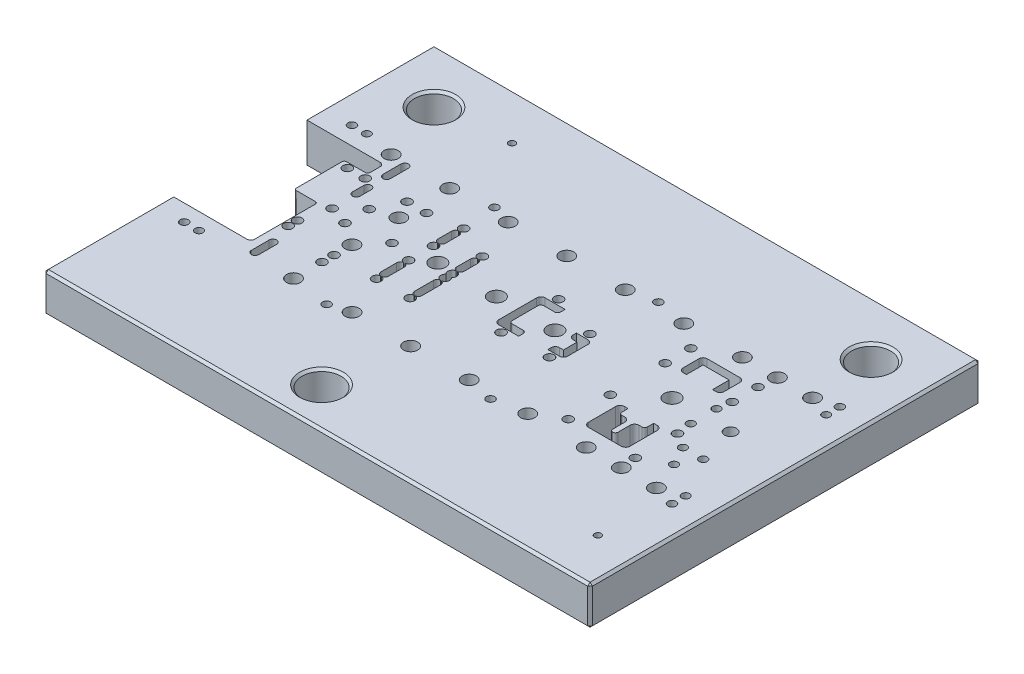
SolidWorks part; units mm, degrees
material "Plain Carbon Steel"
ref_plane "Front Plane" through (0, 0, 0) normal (0, 0, 1) x (1, 0, 0)
ref_plane "Top Plane" through (0, 0, 0) normal (0, 1, 0) x (1, 0, 0)
ref_plane "Right Plane" through (0, 0, 0) normal (1, 0, 0) x (0, 0, -1)
sketch "Sketch1" plane through (0, 0, 0) normal (0, 1, 0) x (1, 0, 0)
  line L1 (-350, -250) -> (350, -250)
  line L2 (-350, -250) -> (-350, 250)
  line L3 (-350, 250) -> (350, 250)
  line L4 (350, -250) -> (350, 250)
  line L5 (-350, -250) -> (350, 250) construction
  line L6 (-350, 250) -> (350, -250) construction
  point P0 (0, 0)
  dimension "D1" = 700
  dimension "D2" = 500
extrude "Boss-Extrude1" add sketch "Sketch1" against normal blind 50
sketch "Sketch2" plane through (0, 0, 0) normal (0, 1, 0) x (1, 0, 0)
  line L0 (350, 250) -> (-350, 250) construction
  line L1 (-350, 250) -> (-350, -250) construction
  line L2 (350, -250) -> (350, 250) construction
  line L3 (-350, -250) -> (350, -250) construction
  circle A0 centre (-280, 180) radius 25
  circle A1 centre (280, 180) radius 25
  circle A2 centre (-44, -200) radius 25
  dimension "D1" = 50
  dimension "D2" = 70
  dimension "D3" = 70
  dimension "D4" = 70
  dimension "D5" = 50
  dimension "D6" = 44
extrude "Cut-Extrude1" cut sketch "Sketch2" against normal up to next
sketch "Sketch3" plane through (0, -50, 0) normal (0, -1, 0) x (1, 0, 0)
  line L0 (178.7436, 30.0264) -> (178.7436, 38.14) construction
  line L1 (182.13, 41.5264) -> (186.13, 41.5264) construction
  line L2 (191.7436, 47.14) -> (191.7436, 62.64) construction
  line L3 (198.5164, 62.64) -> (198.5164, 47.14) construction
  line L4 (204.13, 41.5264) -> (208.13, 41.5264) construction
  line L5 (211.5164, 38.14) -> (211.5164, 30.0264) construction
  line L6 (174.13, 30.0264) -> (178.7436, 30.0264) construction
  line L7 (168.5164, 70.64) -> (168.5164, 35.64) construction
  line L8 (216.13, 76.2536) -> (174.13, 76.2536) construction
  line L9 (211.5164, 30.0264) -> (216.13, 30.0264) construction
  line L10 (221.7436, 35.64) -> (221.7436, 70.64) construction
  line L11 (216.13, -45.0677) -> (211.8377, -45.0677) construction
  line L12 (221.4223, -70.64) -> (221.4223, -50.36) construction
  line L13 (174.13, -75.9323) -> (216.13, -75.9323) construction
  line L14 (178.4223, -45.0677) -> (174.13, -45.0677) construction
  line L15 (168.8377, -50.36) -> (168.8377, -70.64) construction
  line L16 (178.4223, -66.3477) -> (178.4223, -45.0677) construction
  line L17 (211.8377, -66.3477) -> (178.4223, -66.3477) construction
  line L18 (211.8377, -45.0677) -> (211.8377, -66.3477) construction
  line L19 (178.7436, 30.0264) -> (178.7436, 38.14)
  line L20 (182.13, 41.5264) -> (186.13, 41.5264)
  line L21 (191.7436, 47.14) -> (191.7436, 62.64)
  line L22 (198.5164, 62.64) -> (198.5164, 47.14)
  line L23 (204.13, 41.5264) -> (208.13, 41.5264)
  line L24 (211.5164, 38.14) -> (211.5164, 30.0264)
  line L25 (174.13, 30.0264) -> (178.7436, 30.0264)
  line L26 (168.5164, 70.64) -> (168.5164, 35.64)
  line L27 (216.13, 76.2536) -> (174.13, 76.2536)
  line L28 (211.5164, 30.0264) -> (216.13, 30.0264)
  line L29 (221.7436, 35.64) -> (221.7436, 70.64)
  line L30 (216.13, -45.0677) -> (211.8377, -45.0677)
  line L31 (221.4223, -70.64) -> (221.4223, -50.36)
  line L32 (174.13, -75.9323) -> (216.13, -75.9323)
  line L33 (178.4223, -45.0677) -> (174.13, -45.0677)
  line L34 (168.8377, -50.36) -> (168.8377, -70.64)
  line L35 (178.4223, -66.3477) -> (178.4223, -45.0677)
  line L36 (211.8377, -66.3477) -> (178.4223, -66.3477)
  line L37 (211.8377, -45.0677) -> (211.8377, -66.3477)
  line L38 (72.3377, 6.3477) -> (72.3377, -11.0677) construction
  line L39 (67.13, 6.3477) -> (72.3377, 6.3477) construction
  line L40 (61.8377, 15.9323) -> (61.8377, 11.64) construction
  line L41 (72.3377, -11.0677) -> (67.13, -11.0677) construction
  line L42 (61.8377, -16.36) -> (61.8377, -20.6523) construction
  line L43 (76.63, 15.9323) -> (61.8377, 15.9323) construction
  line L44 (81.9223, -15.36) -> (81.9223, 10.64) construction
  line L45 (61.8377, -20.6523) -> (76.63, -20.6523) construction
  line L46 (72.3377, 6.3477) -> (72.3377, -11.0677)
  line L47 (67.13, 6.3477) -> (72.3377, 6.3477)
  line L48 (61.8377, 15.9323) -> (61.8377, 11.64)
  line L49 (72.3377, -11.0677) -> (67.13, -11.0677)
  line L50 (61.8377, -16.36) -> (61.8377, -20.6523)
  line L51 (76.63, 15.9323) -> (61.8377, 15.9323)
  line L52 (81.9223, -15.36) -> (81.9223, 10.64)
  line L53 (61.8377, -20.6523) -> (76.63, -20.6523)
  line L54 (28.4223, 19.9323) -> (2.63, 19.9323) construction
  line L55 (-2.6623, 14.64) -> (-2.6623, -34.36) construction
  line L56 (2.63, -39.6523) -> (28.4223, -39.6523) construction
  line L57 (28.4223, 14.14) -> (28.4223, 19.9323) construction
  line L58 (10.63, 10.3477) -> (24.63, 10.3477) construction
  line L59 (6.9223, -26.36) -> (6.9223, 6.64) construction
  line L60 (24.63, -30.0677) -> (10.63, -30.0677) construction
  line L61 (28.4223, -39.6523) -> (28.4223, -33.86) construction
  line L62 (28.4223, 19.9323) -> (2.63, 19.9323)
  line L63 (-2.6623, 14.64) -> (-2.6623, -34.36)
  line L64 (2.63, -39.6523) -> (28.4223, -39.6523)
  line L65 (28.4223, 14.14) -> (28.4223, 19.9323)
  line L66 (10.63, 10.3477) -> (24.63, 10.3477)
  line L67 (6.9223, -26.36) -> (6.9223, 6.64)
  line L68 (24.63, -30.0677) -> (10.63, -30.0677)
  line L69 (28.4223, -39.6523) -> (28.4223, -33.86)
  line L70 (-131.2322, 36.69) -> (-131.2322, 16.59) construction
  line L71 (-121.5078, 16.59) -> (-121.5078, 36.69) construction
  line L72 (-88.1623, 36.69) -> (-88.1623, 12.59) construction
  line L73 (-78.5777, 12.59) -> (-78.5777, 36.69) construction
  line L74 (-131.1623, -36.31) -> (-131.1623, -53.91) construction
  line L75 (-121.5777, -53.91) -> (-121.5777, -36.31) construction
  line L76 (-88.1623, -17.31) -> (-88.1623, -34.91) construction
  line L77 (-78.5777, -34.91) -> (-78.5777, -17.31) construction
  line L78 (-131.2322, 36.69) -> (-131.2322, 16.59)
  line L79 (-121.5078, 16.59) -> (-121.5078, 36.69)
  line L80 (-88.1623, 36.69) -> (-88.1623, 12.59)
  line L81 (-78.5777, 12.59) -> (-78.5777, 36.69)
  line L82 (-131.1623, -36.31) -> (-131.1623, -53.91)
  line L83 (-121.5777, -53.91) -> (-121.5777, -36.31)
  line L84 (-88.1623, -17.31) -> (-88.1623, -34.91)
  line L85 (-78.5777, -34.91) -> (-78.5777, -17.31)
  line L86 (-238.1623, -72.87) -> (-238.1623, -95.77) construction
  line L87 (-228.5777, -95.77) -> (-228.5777, -72.87) construction
  line L88 (-238.1623, 95.77) -> (-238.1623, 72.87) construction
  line L89 (-228.5777, 72.87) -> (-228.5777, 95.77) construction
  line L90 (-238.1623, -72.87) -> (-238.1623, -95.77)
  line L91 (-228.5777, -95.77) -> (-228.5777, -72.87)
  line L92 (-238.1623, 95.77) -> (-238.1623, 72.87)
  line L93 (-228.5777, 72.87) -> (-228.5777, 95.77)
  line L94 (-228.5777, -48.36) -> (-228.5777, -33.86) construction
  line L95 (-238.1623, -33.86) -> (-238.1623, -48.36) construction
  line L96 (-228.5777, -48.36) -> (-228.5777, -33.86)
  line L97 (-238.1623, -33.86) -> (-238.1623, -48.36)
  arc A0 (182.13, 41.5264) -> (178.7436, 38.14) centre (182.13, 38.14) ccw construction
  arc A1 (186.13, 41.5264) -> (191.7436, 47.14) centre (186.13, 47.14) ccw construction
  arc A2 (198.5164, 62.64) -> (191.7436, 62.64) centre (195.13, 62.64) ccw construction
  arc A3 (198.5164, 47.14) -> (204.13, 41.5264) centre (204.13, 47.14) ccw construction
  arc A4 (211.5164, 38.14) -> (208.13, 41.5264) centre (208.13, 38.14) ccw construction
  arc A5 (168.5164, 35.64) -> (174.13, 30.0264) centre (174.13, 35.64) ccw construction
  arc A6 (174.13, 76.2536) -> (168.5164, 70.64) centre (174.13, 70.64) ccw construction
  arc A7 (221.7436, 70.64) -> (216.13, 76.2536) centre (216.13, 70.64) ccw construction
  arc A8 (216.13, 30.0264) -> (221.7436, 35.64) centre (216.13, 35.64) ccw construction
  arc A9 (221.4223, -50.36) -> (216.13, -45.0677) centre (216.13, -50.36) ccw construction
  arc A10 (216.13, -75.9323) -> (221.4223, -70.64) centre (216.13, -70.64) ccw construction
  arc A11 (168.8377, -70.64) -> (174.13, -75.9323) centre (174.13, -70.64) ccw construction
  arc A12 (174.13, -45.0677) -> (168.8377, -50.36) centre (174.13, -50.36) ccw construction
  arc A13 (182.13, 41.5264) -> (178.7436, 38.14) centre (182.13, 38.14) ccw
  arc A14 (186.13, 41.5264) -> (191.7436, 47.14) centre (186.13, 47.14) ccw
  arc A15 (198.5164, 62.64) -> (191.7436, 62.64) centre (195.13, 62.64) ccw
  arc A16 (198.5164, 47.14) -> (204.13, 41.5264) centre (204.13, 47.14) ccw
  arc A17 (211.5164, 38.14) -> (208.13, 41.5264) centre (208.13, 38.14) ccw
  arc A18 (168.5164, 35.64) -> (174.13, 30.0264) centre (174.13, 35.64) ccw
  arc A19 (174.13, 76.2536) -> (168.5164, 70.64) centre (174.13, 70.64) ccw
  arc A20 (221.7436, 70.64) -> (216.13, 76.2536) centre (216.13, 70.64) ccw
  arc A21 (216.13, 30.0264) -> (221.7436, 35.64) centre (216.13, 35.64) ccw
  arc A22 (221.4223, -50.36) -> (216.13, -45.0677) centre (216.13, -50.36) ccw
  arc A23 (216.13, -75.9323) -> (221.4223, -70.64) centre (216.13, -70.64) ccw
  arc A24 (168.8377, -70.64) -> (174.13, -75.9323) centre (174.13, -70.64) ccw
  arc A25 (174.13, -45.0677) -> (168.8377, -50.36) centre (174.13, -50.36) ccw
  circle A26 centre (270.13, 62.64) radius 5.1136 construction
  circle A27 centre (283.13, 38.14) radius 5.1136 construction
  circle A28 centre (257.13, 38.14) radius 5.1136 construction
  circle A29 centre (235.63, 6.64) radius 5.1136 construction
  circle A30 centre (270.13, -9.86) radius 7.6136 construction
  circle A31 centre (235.63, -26.36) radius 5.1136 construction
  circle A32 centre (270.13, 62.64) radius 5.1136
  circle A33 centre (283.13, 38.14) radius 5.1136
  circle A34 centre (257.13, 38.14) radius 5.1136
  circle A35 centre (235.63, 6.64) radius 5.1136
  circle A36 centre (270.13, -9.86) radius 7.6136
  circle A37 centre (235.63, -26.36) radius 5.1136
  arc A38 (61.8377, 11.64) -> (67.13, 6.3477) centre (67.13, 11.64) ccw construction
  arc A39 (67.13, -11.0677) -> (61.8377, -16.36) centre (67.13, -16.36) ccw construction
  arc A40 (81.9223, 10.64) -> (76.63, 15.9323) centre (76.63, 10.64) ccw construction
  arc A41 (76.63, -20.6523) -> (81.9223, -15.36) centre (76.63, -15.36) ccw construction
  arc A42 (61.8377, 11.64) -> (67.13, 6.3477) centre (67.13, 11.64) ccw
  arc A43 (67.13, -11.0677) -> (61.8377, -16.36) centre (67.13, -16.36) ccw
  arc A44 (81.9223, 10.64) -> (76.63, 15.9323) centre (76.63, 10.64) ccw
  arc A45 (76.63, -20.6523) -> (81.9223, -15.36) centre (76.63, -15.36) ccw
  arc A46 (2.63, 19.9323) -> (-2.6623, 14.64) centre (2.63, 14.64) ccw construction
  arc A47 (-2.6623, -34.36) -> (2.63, -39.6523) centre (2.63, -34.36) ccw construction
  arc A48 (24.63, 10.3477) -> (28.4223, 14.14) centre (24.63, 14.14) ccw construction
  arc A49 (10.63, 10.3477) -> (6.9223, 6.64) centre (10.63, 6.64) ccw construction
  arc A50 (6.9223, -26.36) -> (10.63, -30.0677) centre (10.63, -26.36) ccw construction
  arc A51 (28.4223, -33.86) -> (24.63, -30.0677) centre (24.63, -33.86) ccw construction
  arc A52 (2.63, 19.9323) -> (-2.6623, 14.64) centre (2.63, 14.64) ccw
  arc A53 (-2.6623, -34.36) -> (2.63, -39.6523) centre (2.63, -34.36) ccw
  arc A54 (24.63, 10.3477) -> (28.4223, 14.14) centre (24.63, 14.14) ccw
  arc A55 (10.63, 10.3477) -> (6.9223, 6.64) centre (10.63, 6.64) ccw
  arc A56 (6.9223, -26.36) -> (10.63, -30.0677) centre (10.63, -26.36) ccw
  arc A57 (28.4223, -33.86) -> (24.63, -30.0677) centre (24.63, -33.86) ccw
  arc A58 (-121.5078, 36.69) -> (-131.2322, 36.69) centre (-126.37, 36.69) ccw construction
  arc A59 (-131.2322, 16.59) -> (-121.5078, 16.59) centre (-126.37, 16.59) ccw construction
  arc A60 (-78.5777, 36.69) -> (-88.1623, 36.69) centre (-83.37, 36.69) ccw construction
  arc A61 (-88.1623, 12.59) -> (-78.5777, 12.59) centre (-83.37, 12.59) ccw construction
  arc A62 (-121.5777, -36.31) -> (-131.1623, -36.31) centre (-126.37, -36.31) ccw construction
  arc A63 (-131.1623, -53.91) -> (-121.5777, -53.91) centre (-126.37, -53.91) ccw construction
  arc A64 (-78.5777, -17.31) -> (-88.1623, -17.31) centre (-83.37, -17.31) ccw construction
  arc A65 (-88.1623, -34.91) -> (-78.5777, -34.91) centre (-83.37, -34.91) ccw construction
  arc A66 (-121.5078, 36.69) -> (-131.2322, 36.69) centre (-126.37, 36.69) ccw
  arc A67 (-131.2322, 16.59) -> (-121.5078, 16.59) centre (-126.37, 16.59) ccw
  arc A68 (-78.5777, 36.69) -> (-88.1623, 36.69) centre (-83.37, 36.69) ccw
  arc A69 (-88.1623, 12.59) -> (-78.5777, 12.59) centre (-83.37, 12.59) ccw
  arc A70 (-121.5777, -36.31) -> (-131.1623, -36.31) centre (-126.37, -36.31) ccw
  arc A71 (-131.1623, -53.91) -> (-121.5777, -53.91) centre (-126.37, -53.91) ccw
  arc A72 (-78.5777, -17.31) -> (-88.1623, -17.31) centre (-83.37, -17.31) ccw
  arc A73 (-88.1623, -34.91) -> (-78.5777, -34.91) centre (-83.37, -34.91) ccw
  arc A74 (-228.5777, -72.87) -> (-238.1623, -72.87) centre (-233.37, -72.87) ccw construction
  arc A75 (-238.1623, -95.77) -> (-228.5777, -95.77) centre (-233.37, -95.77) ccw construction
  arc A76 (-228.5777, 95.77) -> (-238.1623, 95.77) centre (-233.37, 95.77) ccw construction
  arc A77 (-238.1623, 72.87) -> (-228.5777, 72.87) centre (-233.37, 72.87) ccw construction
  arc A78 (-228.5777, -72.87) -> (-238.1623, -72.87) centre (-233.37, -72.87) ccw
  arc A79 (-238.1623, -95.77) -> (-228.5777, -95.77) centre (-233.37, -95.77) ccw
  arc A80 (-228.5777, 95.77) -> (-238.1623, 95.77) centre (-233.37, 95.77) ccw
  arc A81 (-238.1623, 72.87) -> (-228.5777, 72.87) centre (-233.37, 72.87) ccw
  arc A82 (-228.5777, -33.86) -> (-238.1623, -33.86) centre (-233.37, -33.86) ccw construction
  arc A83 (-238.1623, -48.36) -> (-228.5777, -48.36) centre (-233.37, -48.36) ccw construction
  arc A84 (-228.5777, -33.86) -> (-238.1623, -33.86) centre (-233.37, -33.86) ccw
  arc A85 (-238.1623, -48.36) -> (-228.5777, -48.36) centre (-233.37, -48.36) ccw
extrude "Cut-Extrude2" cut sketch "Sketch3" against normal up to next
sketch "Sketch4" plane through (0, 0, 0) normal (0, 1, 0) x (1, 0, 0)
  circle A0 centre (-29.87, -100) radius 9 construction
  circle A1 centre (45.13, -100) radius 9 construction
  circle A2 centre (120.13, -100) radius 9 construction
  circle A3 centre (-104.87, 9.86) radius 10 construction
  circle A4 centre (-29.87, 9.86) radius 10 construction
  circle A5 centre (45.13, 9.86) radius 10 construction
  circle A6 centre (195.13, 9.86) radius 10 construction
  circle A7 centre (-104.87, 100) radius 9 construction
  circle A8 centre (-29.87, 100) radius 9 construction
  circle A9 centre (45.13, 100) radius 9 construction
  circle A10 centre (120.13, 100) radius 9 construction
  circle A11 centre (195.13, 100) radius 9 construction
  circle A12 centre (240, 100) radius 9 construction
  circle A13 centre (285, 100) radius 9 construction
  circle A14 centre (195.13, -100) radius 9 construction
  circle A15 centre (240, -100) radius 9 construction
  circle A16 centre (285, -100) radius 9 construction
  circle A17 centre (-29.87, -100) radius 9
  circle A18 centre (45.13, -100) radius 9
  circle A19 centre (120.13, -100) radius 9
  circle A20 centre (-104.87, 9.86) radius 10
  circle A21 centre (-29.87, 9.86) radius 10
  circle A22 centre (45.13, 9.86) radius 10
  circle A23 centre (195.13, 9.86) radius 10
  circle A24 centre (-104.87, 100) radius 9
  circle A25 centre (-29.87, 100) radius 9
  circle A26 centre (45.13, 100) radius 9
  circle A27 centre (120.13, 100) radius 9
  circle A28 centre (195.13, 100) radius 9
  circle A29 centre (240, 100) radius 9
  circle A30 centre (285, 100) radius 9
  circle A31 centre (195.13, -100) radius 9
  circle A32 centre (240, -100) radius 9
  circle A33 centre (285, -100) radius 9
  circle A34 centre (-179.87, -25.14) radius 9 construction
  circle A35 centre (-179.87, 100) radius 9
  circle A36 centre (-179.87, 100) radius 9
  circle A37 centre (-179.87, -100) radius 9
  circle A38 centre (-179.87, -100) radius 9
  circle A39 centre (-104.87, -100) radius 9
  circle A40 centre (-104.87, -100) radius 9
  circle A41 centre (-254.87, 100) radius 9
  circle A42 centre (-254.87, 100) radius 9
  circle A43 centre (-179.87, 34.86) radius 9 construction
  circle A44 centre (-179.87, -25.14) radius 9
  circle A45 centre (-179.87, 34.86) radius 9
  dimension "D1" = 0
  dimension "D2" = 0
  dimension "D3" = 0
  dimension "D4" = 0
extrude "Cut-Extrude3" cut sketch "Sketch4" against normal blind 23
hole_wizard "Ø11.5 (11.5) Diameter Hole1" positions "Sketch8" profile "Sketch7" hole size "Ø11.5" standard "ISO" end condition through all
sketch "Sketch8" plane through (0, -50, 0) normal (0, -1, 0) x (-1, 0, 0)
  point P0 (267.87, 56.92)
  point P3 (245.0007, 56.92)
  point P6 (232.87, 2.36)
  point P9 (208.37, -5.64)
  point P12 (208.37, 25.36)
  point P15 (241.62, -33.14)
  point P18 (241.62, -45.14)
  point P21 (179.87, -48.14)
  point P24 (179.87, -63.64)
  point P27 (192.37, 57.86)
  point P30 (167.37, 57.86)
  point P33 (126.37, 64.36)
  point P36 (126.37, 25.86)
  point P39 (126.37, -47.14)
  point P42 (126.37, -6.14)
  point P45 (156.12, 2.36)
  point P48 (83.37, -47.14)
  point P51 (83.37, -2.14)
  point P54 (83.37, 6.86)
  point P57 (83.37, 45.36)
  point P60 (-12.94, -26.9862)
  point P63 (-12.94, 46.7062)
  point P66 (-71.5, 28.2062)
  point P69 (-71.5, -23.4862)
  point P72 (-152.13, -80.14)
  point P75 (-152.13, -26.14)
  point P78 (-238.13, -80.14)
  point P81 (-238.13, -26.14)
  point P84 (-152.13, 44)
  point P87 (-152.13, 77)
  point P90 (-238.13, 44)
  point P93 (-238.13, 77)
sketch "Sketch7" plane through (-267.87, -50, -56.92) normal (1, 0, 0) x (0, 0, -1)
  line L0 (0, 0) -> (0, 50)
  line L1 (0, 50) -> (5.75, 50)
  line L2 (5.75, 50) -> (5.75, 0)
  line L5 (5.75, 0) -> (0, 0)
  line L11 (0, -6.35) -> (0, 107.95) construction
  dimension "Thru Hole Dia." = 11.5
  dimension "Thru Hole Depth" = 50
hole_wizard "CBORE for M10 Hex Socket Head Cap Screw1" positions "Sketch17" profile "Sketch12" counterbore size "M10" standard "ISO" end condition through all
sketch "Sketch17" plane through (0, -50, 0) normal (0, -1, 0) x (-1, 0, 0)
  point P0 (-312.5, 107.5)
  point P15 (-80, 107.5)
  point P18 (-80, -107.5)
  point P21 (130, -107.5)
  point P26 (-312.5, -107.5)
  point P31 (130, 107.5)
  point P35 (312.5, 107.5)
  point P40 (312.5, -107.5)
sketch "Sketch12" plane through (312.5, -50, -107.5) normal (1, 0, 0) x (0, 0, -1)
  line L0 (0, 0) -> (0, 50)
  line L1 (0, 50) -> (5.25, 50)
  line L3 (5.25, 50) -> (5.25, 10.6)
  line L4 (5.25, 10.6) -> (9, 10.6)
  line L5 (9, 10.6) -> (9, 0)
  line L7 (9, 0) -> (0, 0)
  line L11 (0, -6.35) -> (0, 107.95) construction
  dimension "Thru Hole Dia." = 10.5
  dimension "Thru Hole Depth" = 50
  dimension "C'Bore Dia." = 18
  dimension "C'Bore Depth" = 10.6
hole_wizard "Ø10.0mm Dowel Hole1" positions "Sketch16" profile "Sketch15" hole size "Ø10.0" standard "ISO" end condition through all
sketch "Sketch16" plane through (0, -50, 0) normal (0, -1, 0) x (-1, 0, 0)
  point P0 (-312.5, 90)
  point P3 (-312.5, -90)
  point P6 (293.5, -107.5)
  point P9 (293.5, 107.5)
sketch "Sketch15" plane through (312.5, -50, -90) normal (1, 0, 0) x (0, 0, -1)
  line L0 (0, 0) -> (0, 50)
  line L1 (0, 50) -> (5, 50)
  line L2 (5, 50) -> (5, 0)
  line L5 (5, 0) -> (0, 0)
  line L11 (0, -6.35) -> (0, 107.95) construction
  dimension "Thru Hole Dia." = 10
  dimension "Thru Hole Depth" = 50
sketch "Sketch20" plane through (0, 0, 0) normal (0, 1, 0) x (1, 0, 0)
  line L0 (-350, 250) -> (-350, -250) construction
  line L1 (-350, 84.36) -> (-350, -86.2624)
  line L2 (-251.37, -0.64) -> (-275.37, -0.64) construction
  line L4 (-251.37, -0.64) -> (-275.37, -0.64)
  line L8 (-253.37, 84.36) -> (-325, 84.36) construction
  line L9 (-248.37, 66.48) -> (-248.37, 79.36) construction
  line L10 (-275.37, 63.48) -> (-251.37, 63.48) construction
  line L11 (-278.37, 2.36) -> (-278.37, 60.48) construction
  line L13 (-325, -86.2624) -> (-253.37, -86.2624) construction
  line L14 (-248.37, -81.2624) -> (-248.37, -3.64) construction
  line L15 (-253.37, 84.36) -> (-350, 84.36)
  line L16 (-248.37, 66.48) -> (-248.37, 79.36)
  line L17 (-275.37, 63.48) -> (-251.37, 63.48)
  line L18 (-278.37, 2.36) -> (-278.37, 60.48)
  line L20 (-350, -86.2624) -> (-253.37, -86.2624)
  line L21 (-248.37, -81.2624) -> (-248.37, -3.64)
  arc A0 (-248.37, 79.36) -> (-253.37, 84.36) centre (-253.37, 79.36) ccw construction
  arc A1 (-251.37, 63.48) -> (-248.37, 66.48) centre (-251.37, 66.48) ccw construction
  arc A2 (-275.37, 63.48) -> (-278.37, 60.48) centre (-275.37, 60.48) ccw construction
  arc A4 (-248.37, -3.64) -> (-251.37, -0.64) centre (-251.37, -3.64) ccw construction
  arc A5 (-253.37, -86.2624) -> (-248.37, -81.2624) centre (-253.37, -81.2624) ccw construction
  arc A6 (-248.37, 79.36) -> (-253.37, 84.36) centre (-253.37, 79.36) ccw
  arc A7 (-251.37, 63.48) -> (-248.37, 66.48) centre (-251.37, 66.48) ccw
  arc A8 (-275.37, 63.48) -> (-278.37, 60.48) centre (-275.37, 60.48) ccw
  arc A10 (-248.37, -3.64) -> (-251.37, -0.64) centre (-251.37, -3.64) ccw
  arc A11 (-253.37, -86.2624) -> (-248.37, -81.2624) centre (-253.37, -81.2624) ccw
  arc A12 (-278.37, 2.36) -> (-275.37, -0.64) centre (-275.37, 2.36) ccw construction
  arc A13 (-278.37, 2.36) -> (-275.37, -0.64) centre (-275.37, 2.36) ccw
extrude "Cut-Extrude4" cut sketch "Sketch20" against normal up to next
chamfer "Chamfer1" distance 3 angle 45 6 edges at (280, -50, -205) (280, 0, -155) (-280, -50, -205) (-280, 0, -155) (-44, -50, 175) (-44, 0, 225)
chamfer "Chamfer2" distance 3 angle 45 16 edges at (0, -50, -250) (0, 0, -250) (350, -25, -250) (350, -50, 0) (350, 0, 0) (350, -25, 250) (0, -50, 250) (0, 0, 250) (-350, -25, 250) (-350, -50, -167.18) (-350, -50, 168.1312) (-350, -25, -250) (-350, 0, 168.1312) (-350, 0, -167.18) (-350, -25, 86.2624) (-350, -25, -84.36)
hole_wizard "M10 Tapped Hole1" positions "Sketch25" profile "Sketch22" tap size "M10" standard "ISO"
sketch "Sketch25" plane through (0, 0, 0) normal (0, 1, 0) x (1, 0, 0)
  line L0 (350, 247) -> (350, -247) construction
  line L1 (347, -250) -> (-347, -250) construction
  line L2 (-347, 250) -> (347, 250) construction
  line L3 (-350, 87.36) -> (-350, 247) construction
  point P0 (300, -190)
  point P7 (-190, 190)
  dimension "D1" = 50
  dimension "D2" = 60
  dimension "D3" = 60
  dimension "D4" = 160
sketch "Sketch22" plane through (300, 0, 190) normal (1, 0, 0) x (0, 0, 1)
  line L0 (0, 0) -> (0, 30.0537)
  line L1 (0, 30.0537) -> (4.25, 27.5)
  line L2 (4.25, 27.5) -> (4.25, 0)
  line L5 (4.25, 0) -> (0, 0)
  line L10 (0, 30.0537) -> (-4.25, 27.5) construction
  line L11 (0, -6.35) -> (0, 107.95) construction
  dimension "Tap Drill Dia." = 8.5
  dimension "Tap Drill Depth" = 27.5
  dimension "Drill Angle" = 118
cosmetic thread "Hole Thread1"
cosmetic thread "Hole Thread2"
